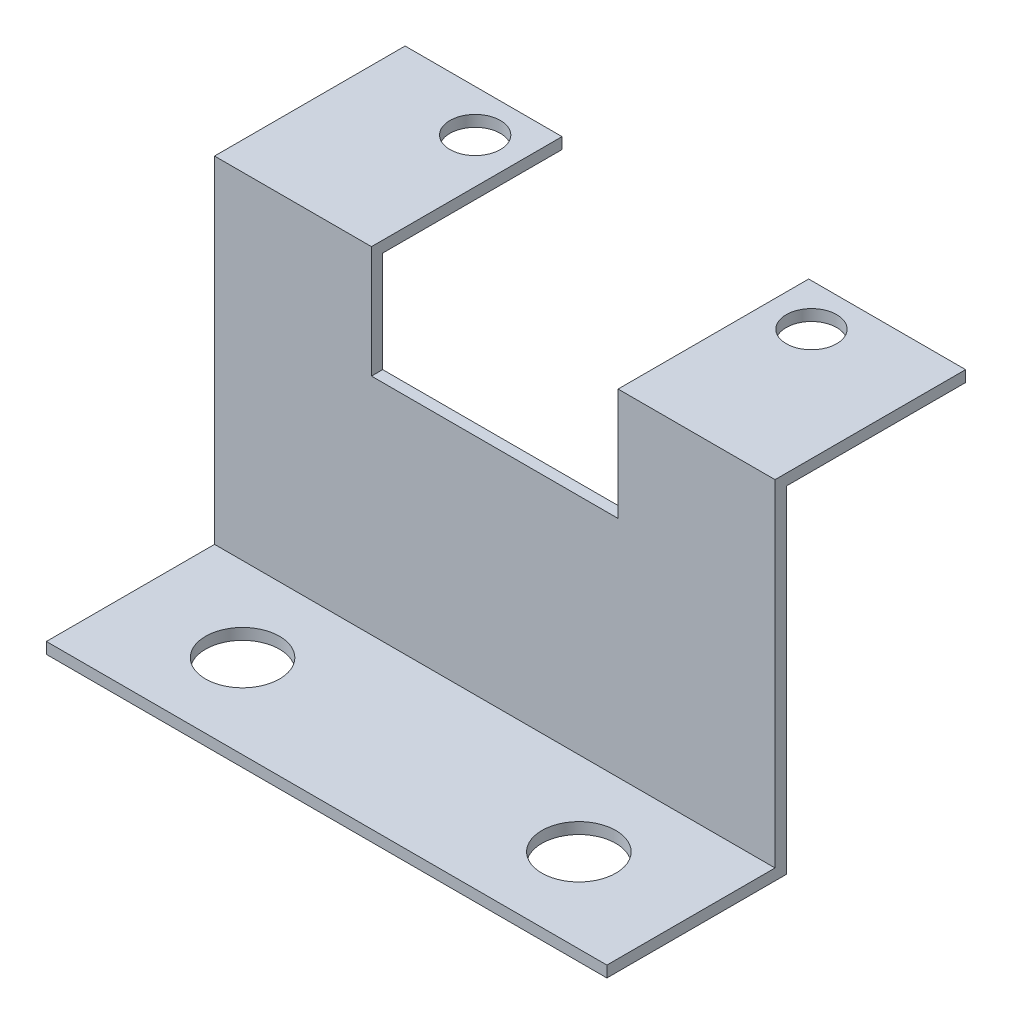
SolidWorks part; units mm, degrees
ref_plane "Front Plane" through (0, 0, 0) normal (0, 0, 1) x (1, 0, 0)
ref_plane "Top Plane" through (0, 0, 0) normal (0, 1, 0) x (1, 0, 0)
ref_plane "Right Plane" through (0, 0, 0) normal (1, 0, 0) x (0, 0, -1)
sketch "Sketch1" plane through (0, 0, 0) normal (1, 0, 0) x (0, 0, -1)
  line L0 (0, 0) -> (16, 0)
  line L1 (16, 0) -> (16, 30)
  line L2 (16, 30) -> (32, 30)
  line L3 (0, 1) -> (15, 1)
  line L4 (15, 1) -> (15, 31)
  line L5 (15, 31) -> (32, 31)
  line L6 (0, 0) -> (0, 1)
  line L7 (32, 30) -> (32, 31)
  dimension "D1" = 16
  dimension "D2" = 16
  dimension "D3" = 30
  dimension "D4" = 1
extrude "Boss-Extrude1" add sketch "Sketch1" along normal mid plane 50
sketch "Sketch2" plane through (0, 31, 0) normal (0, 1, 0) x (1, 0, 0)
  line L0 (25, 15) -> (-25, 15) construction
  line L1 (-11, 15) -> (11, 15)
  line L2 (-11, 15) -> (-11, 32)
  line L3 (-11, 32) -> (11, 32)
  line L4 (11, 15) -> (11, 32)
  line L5 (25, 32) -> (-25, 32) construction
  line L6 (-15, 28.25) -> (15, 28.25) construction
  line L7 (-15, 7.5) -> (15, 7.5) construction
  line L9 (-25, 15) -> (-25, 0) construction
  point P8 (0, 15)
  point P12 (0, 28.25)
  point P15 (0, 7.5)
  point P18 (-25, 7.5)
  dimension "D1" = 22
  dimension "D2" = 30
  dimension "D3" = 3.75
extrude "Cut-Extrude1" cut sketch "Sketch2" against normal blind 10
hole_wizard "M4 Clearance Hole1" positions "Sketch3" profile "Sketch4" hole size "M4" standard "ISO" end condition through all
sketch "Sketch3" plane through (0, 31, 0) normal (0, 1, 0) x (1, 0, 0)
  point P0 (-15, 28.25)
  point P3 (15, 28.25)
sketch "Sketch4" plane through (-15, 31, -28.25) normal (1, 0, 0) x (0, 0, 1)
  line L0 (0, 0) -> (0, 31)
  line L1 (0, 31) -> (2.25, 31)
  line L2 (2.25, 31) -> (2.25, 0)
  line L5 (2.25, 0) -> (0, 0)
  line L11 (0, -6.35) -> (0, 107.95) construction
  dimension "Thru Hole Dia." = 4.5
  dimension "Thru Hole Depth" = 31
hole_wizard "M6 Clearance Hole1" positions "Sketch5" profile "Sketch6" hole size "M6" standard "ISO" end condition through all
sketch "Sketch5" plane through (0, 1, 0) normal (0, 1, 0) x (1, 0, 0)
  point P0 (-15, 7.5)
  point P3 (15, 7.5)
sketch "Sketch6" plane through (-15, 1, -7.5) normal (1, 0, 0) x (0, 0, 1)
  line L0 (0, 0) -> (0, 1)
  line L1 (0, 1) -> (3.3, 1)
  line L2 (3.3, 1) -> (3.3, 0)
  line L5 (3.3, 0) -> (0, 0)
  line L11 (0, -6.35) -> (0, 107.95) construction
  dimension "Thru Hole Dia." = 6.6
  dimension "Thru Hole Depth" = 1
